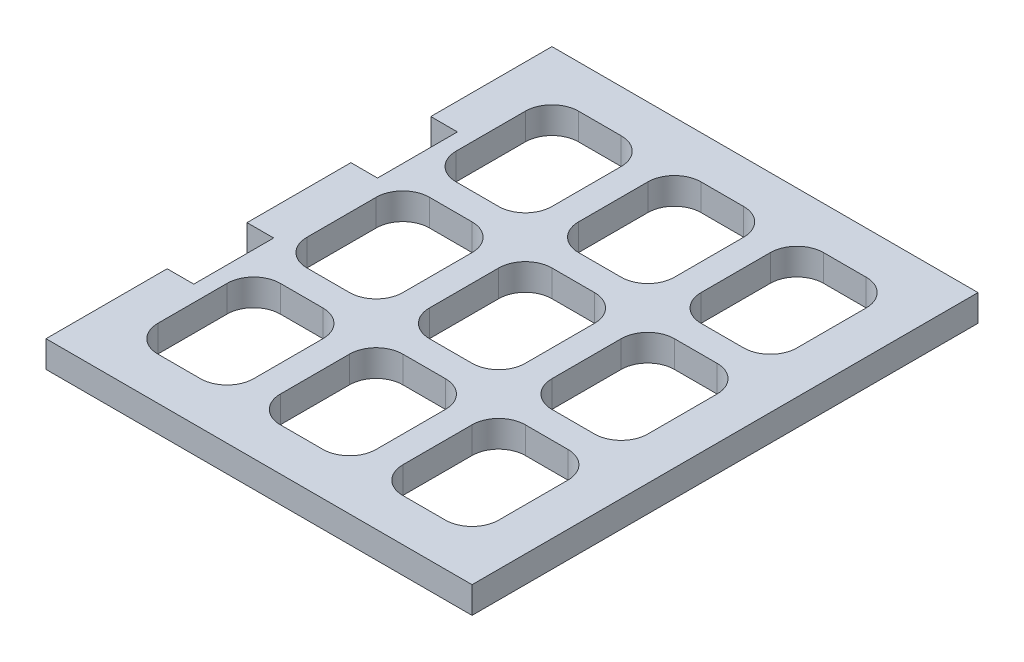
SolidWorks part; units mm, degrees
ref_plane "정면" through (0, 0, 0) normal (0, 0, 1) x (1, 0, 0)
ref_plane "윗면" through (0, 0, 0) normal (0, 1, 0) x (1, 0, 0)
ref_plane "우측면" through (0, 0, 0) normal (1, 0, 0) x (0, 0, -1)
sketch "스케치1" plane through (0, 0, 0) normal (0, 1, 0) x (1, 0, 0)
  line L1 (-40, -47.5) -> (40, -47.5)
  line L2 (-40, -47.5) -> (-40, 47.5)
  line L3 (-40, 47.5) -> (40, 47.5)
  line L4 (40, -47.5) -> (40, 47.5)
  line L5 (-40, -47.5) -> (40, 47.5) construction
  line L6 (-40, 47.5) -> (40, -47.5) construction
  point P0 (0, 0)
  dimension "D1" = 80
  dimension "D2" = 95
extrude "보스-돌출1" add sketch "스케치1" along normal blind 5
sketch "스케치2" plane through (0, 5, 0) normal (0, 1, 0) x (1, 0, 0)
  point P0 (0, 0)
sketch3d "3D스케치1"
  line L0 (0, 5, 0) -> (0, 158, 0) construction
hole_wizard "M3x0.5 나사 구멍1" [suppressed] positions "스케치7" profile "스케치6" tap size "M3x0.5" standard "Ansi Metric"
sketch "스케치7" plane through (-40, 0, 0) normal (-1, 0, 0) x (0, 0, 1)
  line L0 (47.5, 2.5) -> (12.5, 2.5) construction
  line L1 (47.5, 5) -> (47.5, 0) construction
  line L2 (12.5, 2.5) -> (-12.5, 2.5) construction
  line L3 (-12.5, 2.5) -> (-47.5, 2.5) construction
  line L4 (-47.5, 5) -> (-47.5, 0) construction
  point P2 (12.5, 2.5)
  point P6 (-12.5, 2.5)
  dimension "D1" = 25
sketch "스케치6" plane through (-40, 2.5, 12.5) normal (0, 1, 0) x (0, 0, 1)
  line L0 (0, 0) -> (0, 15.7511)
  line L1 (0, 15.7511) -> (1.25, 15)
  line L2 (1.25, 15) -> (1.25, 0)
  line L5 (1.25, 0) -> (0, 0)
  line L10 (0, 15.7511) -> (-1.25, 15) construction
  line L11 (0, -6.35) -> (0, 107.95) construction
  dimension "탭 드릴 지름" = 2.5
  dimension "탭 드릴 깊이" = 15
  dimension "드릴 각도" = 118
cosmetic thread "구멍 나사산1" [suppressed] parameters "D1"=6, "D2"=3
cosmetic thread "구멍 나사산2" [suppressed] parameters "D1"=6, "D2"=3
sketch "스케치9" plane through (0, 5, 0) normal (0, 1, 0) x (1, 0, 0)
  line L0 (-40, 47.5) -> (-40, -47.5) construction
  line L1 (-32, 39.5) -> (32, 39.5) construction
  line L2 (-32, 39.5) -> (-32, -39.5) construction
  line L3 (-32, -39.5) -> (32, -39.5) construction
  line L4 (32, 39.5) -> (32, -39.5) construction
  line L5 (40, 47.5) -> (-40, 47.5) construction
  line L6 (-14, 16.5) -> (-9, 16.5) construction
  line L7 (-27, 39.5) -> (-19, 39.5)
  line L8 (-32, 34.5) -> (-32, 21.5)
  line L9 (-27, 16.5) -> (-19, 16.5)
  line L10 (-14, 34.5) -> (-14, 21.5)
  line L11 (14, 34.5) -> (14, 21.5)
  line L12 (9, 16.5) -> (14, 16.5) construction
  line L13 (4, 39.5) -> (-4, 39.5)
  line L14 (9, 34.5) -> (9, 21.5)
  line L15 (4, 16.5) -> (-4, 16.5)
  line L16 (-9, 34.5) -> (-9, 21.5)
  line L17 (27, 39.5) -> (19, 39.5)
  line L18 (32, 34.5) -> (32, 21.5)
  line L19 (19, 16.5) -> (27, 16.5)
  line L21 (40, -47.5) -> (40, 47.5) construction
  line L22 (-14, 16.5) -> (-14, 11.5) construction
  line L23 (-14, -11.5) -> (-14, -16.5) construction
  line L24 (-40, -47.5) -> (40, -47.5) construction
  line L25 (-19, -16.5) -> (-27, -16.5)
  line L26 (-14, -21.5) -> (-14, -34.5)
  line L27 (-19, -39.5) -> (-27, -39.5)
  line L28 (-32, -21.5) -> (-32, -34.5)
  line L29 (-19, 11.5) -> (-27, 11.5)
  line L30 (-14, 6.5) -> (-14, -6.5)
  line L31 (-19, -11.5) -> (-27, -11.5)
  line L32 (-32, 6.5) -> (-32, -6.5)
  line L33 (-14, 11.5) -> (-9, 11.5) construction
  line L34 (-4, 11.5) -> (4, 11.5)
  line L35 (-9, 6.5) -> (-9, -6.5)
  line L36 (-4, -11.5) -> (4, -11.5)
  line L37 (9, 6.5) -> (9, -6.5)
  line L38 (19, 11.5) -> (27, 11.5)
  line L39 (14, 6.5) -> (14, -6.5)
  line L40 (19, -11.5) -> (27, -11.5)
  line L41 (32, 6.5) -> (32, -6.5)
  line L42 (-4, -16.5) -> (4, -16.5)
  line L43 (-9, -21.5) -> (-9, -34.5)
  line L44 (-4, -39.5) -> (4, -39.5)
  line L45 (9, -21.5) -> (9, -34.5)
  line L46 (19, -16.5) -> (27, -16.5)
  line L47 (14, -21.5) -> (14, -34.5)
  line L48 (19, -39.5) -> (27, -39.5)
  line L49 (32, -21.5) -> (32, -34.5)
  line L50 (-9, 16.5) -> (-9, 11.5) construction
  line L51 (-14, -16.5) -> (-9, -16.5) construction
  line L52 (-9, -16.5) -> (-9, -11.5) construction
  line L53 (-9, -11.5) -> (-14, -11.5) construction
  line L54 (9, 16.5) -> (9, 11.5) construction
  line L55 (9, -11.5) -> (9, -16.5) construction
  line L56 (14, 11.5) -> (14, 16.5) construction
  line L57 (14, -11.5) -> (14, -16.5) construction
  line L58 (14, -16.5) -> (9, -16.5) construction
  line L59 (9, -11.5) -> (14, -11.5) construction
  line L60 (14, 11.5) -> (9, 11.5) construction
  arc A0 (27, 11.5) -> (32, 6.5) centre (27, 6.5) cw
  arc A1 (19, 11.5) -> (14, 6.5) centre (19, 6.5) ccw
  arc A2 (4, 11.5) -> (9, 6.5) centre (4, 6.5) cw
  arc A3 (19, -16.5) -> (14, -21.5) centre (19, -21.5) ccw
  arc A4 (4, -16.5) -> (9, -21.5) centre (4, -21.5) cw
  arc A5 (4, -11.5) -> (9, -6.5) centre (4, -6.5) ccw
  arc A6 (14, -6.5) -> (19, -11.5) centre (19, -6.5) ccw
  arc A7 (27, -11.5) -> (32, -6.5) centre (27, -6.5) ccw
  arc A8 (27, -16.5) -> (32, -21.5) centre (27, -21.5) cw
  arc A9 (27, -39.5) -> (32, -34.5) centre (27, -34.5) ccw
  arc A10 (14, -34.5) -> (19, -39.5) centre (19, -34.5) ccw
  arc A11 (4, -39.5) -> (9, -34.5) centre (4, -34.5) ccw
  arc A12 (-9, -34.5) -> (-4, -39.5) centre (-4, -34.5) ccw
  arc A13 (-14, -34.5) -> (-19, -39.5) centre (-19, -34.5) cw
  arc A14 (-27, -39.5) -> (-32, -34.5) centre (-27, -34.5) cw
  arc A15 (-4, -16.5) -> (-9, -21.5) centre (-4, -21.5) ccw
  arc A16 (-19, -16.5) -> (-14, -21.5) centre (-19, -21.5) cw
  arc A17 (-9, -6.5) -> (-4, -11.5) centre (-4, -6.5) ccw
  arc A18 (-14, -6.5) -> (-19, -11.5) centre (-19, -6.5) cw
  arc A19 (-4, 11.5) -> (-9, 6.5) centre (-4, 6.5) ccw
  arc A20 (-19, 11.5) -> (-14, 6.5) centre (-19, 6.5) cw
  arc A21 (-19, 16.5) -> (-14, 21.5) centre (-19, 21.5) ccw
  arc A22 (-4, 16.5) -> (-9, 21.5) centre (-4, 21.5) cw
  arc A23 (9, 21.5) -> (4, 16.5) centre (4, 21.5) cw
  arc A24 (14, 21.5) -> (19, 16.5) centre (19, 21.5) ccw
  arc A25 (32, 21.5) -> (27, 16.5) centre (27, 21.5) cw
  arc A26 (27, 39.5) -> (32, 34.5) centre (27, 34.5) cw
  arc A27 (19, 39.5) -> (14, 34.5) centre (19, 34.5) ccw
  arc A28 (4, 39.5) -> (9, 34.5) centre (4, 34.5) cw
  arc A29 (-4, 39.5) -> (-9, 34.5) centre (-4, 34.5) ccw
  arc A30 (-19, 39.5) -> (-14, 34.5) centre (-19, 34.5) cw
  arc A31 (-27, -16.5) -> (-32, -21.5) centre (-27, -21.5) ccw
  arc A32 (-27, -11.5) -> (-32, -6.5) centre (-27, -6.5) cw
  arc A33 (-27, 11.5) -> (-32, 6.5) centre (-27, 6.5) ccw
  arc A34 (-32, 21.5) -> (-27, 16.5) centre (-27, 21.5) ccw
  arc A35 (-27, 39.5) -> (-32, 34.5) centre (-27, 34.5) ccw
  point P66 (32, -11.5)
  point P76 (9, -39.5)
  point P123 (9, 39.5)
  point P128 (-14, 39.5)
  point P133 (-32, -11.5)
  point P138 (-32, 16.5)
  dimension "D3" = 8
  dimension "D9" = 5
  dimension "D1" = 8
  dimension "D2" = 8
  dimension "D4" = 5
  dimension "D5" = 18
  dimension "D6" = 5
  dimension "D7" = 8
  dimension "D8" = 23
extrude "컷-돌출2" cut sketch "스케치9" against normal blind 10
hole_wizard "M3x0.5 나사 구멍2" [suppressed] positions "스케치11" profile "스케치10" tap size "M3x0.5" standard "Ansi Metric"
sketch "스케치11" plane through (0, 5, 0) normal (0, 1, 0) x (1, 0, 0)
  line L2 (-45, 45) -> (-45, -71) construction
  line L4 (45, 45) -> (45, -45) construction
  line L5 (-45, 45) -> (-50, 45) construction
  line L6 (-50, 50) -> (-50, -50) construction
  line L9 (-45, 45) -> (-45, 50) construction
  line L10 (50, 50) -> (-50, 50) construction
  line L13 (50, -45) -> (45, -45) construction
  line L14 (50, -50) -> (50, 50) construction
  line L15 (45, -45) -> (45, -50) construction
  line L16 (-50, -50) -> (50, -50) construction
  line L17 (-45, 45) -> (16.5, 45) construction
  line L18 (16.5, 45) -> (77.5, 45) construction
  line L19 (77.5, 45) -> (45, 45) construction
  line L21 (-92, -45) -> (16.5, -45) construction
  line L22 (16.5, -45) -> (77.5, -45) construction
  line L23 (77.5, -45) -> (45, -45) construction
  line L25 (16.5, 45) -> (16.5, -45) construction
  line L28 (77.5, 45) -> (77.5, -45) construction
  point P0 (-45, 45)
  point P1 (45, -45)
  point P122 (-45, -71)
  point P123 (45, 45)
  point P191 (16.5, 45)
  point P193 (77.5, 45)
  point P195 (77.5, -45)
  point P196 (16.5, -45)
  dimension "D1" = 5
  dimension "D2" = 61.5
  dimension "D3" = 61
sketch "스케치10" plane through (-45, 5, -45) normal (1, 0, 0) x (0, 0, 1)
  line L0 (0, 0) -> (0, 15.7511)
  line L1 (0, 15.7511) -> (1.25, 15)
  line L2 (1.25, 15) -> (1.25, 0)
  line L5 (1.25, 0) -> (0, 0)
  line L10 (0, 15.7511) -> (-1.25, 15) construction
  line L11 (0, -6.35) -> (0, 107.95) construction
  dimension "탭 드릴 지름" = 2.5
  dimension "탭 드릴 깊이" = 15
  dimension "드릴 각도" = 118
cosmetic thread "구멍 나사산3" [suppressed] parameters "D1"=5, "D2"=3
cosmetic thread "구멍 나사산5" [suppressed] parameters "D1"=5, "D2"=3
cosmetic thread "구멍 나사산6" [suppressed] parameters "D1"=5, "D2"=3
cosmetic thread "구멍 나사산7" [suppressed] parameters "D1"=5, "D2"=3
cosmetic thread "구멍 나사산10" [suppressed] parameters "D1"=5, "D2"=3
sketch "스케치12" plane through (0, 0, 0) normal (0, -1, 0) x (1, 0, 0)
  line L1 (-35, -46.25) -> (35, -46.25) construction
  line L2 (-35, -46.25) -> (-35, 46.25) construction
  line L3 (-35, 46.25) -> (35, 46.25) construction
  line L4 (35, -46.25) -> (35, 46.25) construction
  line L5 (-35, -46.25) -> (35, 46.25) construction
  line L6 (-35, 46.25) -> (35, -46.25) construction
  point P0 (0, 0)
  dimension "D1" = 70
  dimension "D2" = 92.5
hole_wizard "M3 납작 머리 작은 나사용 카운터싱크1" [suppressed] positions "스케치17" profile "스케치15" countersink size "M3" standard "Ansi Metric"
sketch "스케치17" plane through (0, 0, 0) normal (0, -1, 0) x (-1, 0, 0)
  line L0 (37.4935, -47.5) -> (37.4935, -12.5) construction
  line L1 (40, -47.5) -> (-40, -47.5) construction
  line L2 (37.4935, -12.5) -> (37.4935, 12.5) construction
  line L3 (37.4935, 12.5) -> (37.4935, 47.5) construction
  line L4 (-40, 47.5) -> (40, 47.5) construction
  point P2 (37.4935, -12.5)
  point P5 (37.4935, 12.5)
  dimension "D1" = 25
sketch "스케치15" plane through (-37.4935, 0, 12.5) normal (1, 0, 0) x (0, 0, -1)
  line L0 (0, 0) -> (0, 5)
  line L1 (0, 5) -> (1.7, 5)
  line L2 (1.7, 5) -> (1.7, 1.45)
  line L3 (1.7, 1.45) -> (3.15, 0)
  line L5 (3.15, 0) -> (0, 0)
  line L6 (-1.7, 1.45) -> (-3.15, 0) construction
  line L11 (0, -6.35) -> (0, 107.95) construction
  dimension "관통 구멍 지름" = 3.4
  dimension "관통 구멍 깊이" = 5
  dimension "표면 카운터싱크 지름" = 6.3
  dimension "표면 카운터싱크 각도" = 90
sketch "스케치18" plane through (0, 0, 0) normal (0, -1, 0) x (1, 0, 0)
  line L1 (-40, 0) -> (-35, 0) construction
  line L2 (-40, -47.5) -> (-40, 47.5) construction
  line L3 (-35, -46.25) -> (-35, 46.25) construction
  line L4 (-35, 0) -> (-35, 9.75) construction
  line L7 (-35, 0) -> (-35, -9.75) construction
  line L9 (-35, -9.75) -> (-40, -9.75)
  line L10 (-35, -9.75) -> (-35, -24.75)
  line L12 (-35, -24.75) -> (-40, -24.75)
  line L13 (-40, -9.75) -> (-40, -24.75)
  line L14 (-35, 9.75) -> (-40, 9.75)
  line L15 (-35, 9.75) -> (-35, 24.75)
  line L16 (-35, 24.75) -> (-40, 24.75)
  line L17 (-40, 9.75) -> (-40, 24.75)
  dimension "D1" = 19.5
  dimension "D2" = 15
extrude "컷-돌출4" cut sketch "스케치18" against normal blind 10
